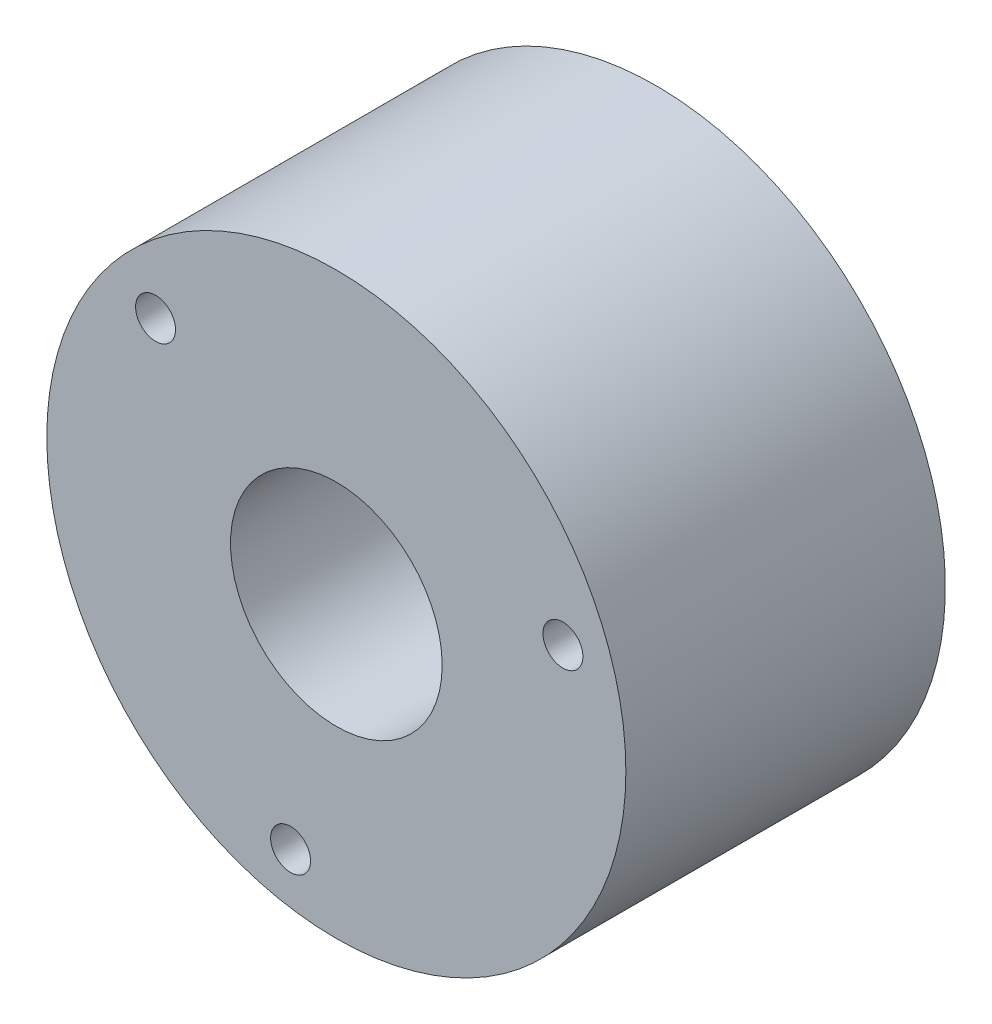
SolidWorks part; units mm, degrees
ref_plane "Ön Düzlem" through (0, 0, 0) normal (0, 0, 1) x (1, 0, 0)
ref_plane "Üst Düzlem" through (0, 0, 0) normal (0, 1, 0) x (1, 0, 0)
ref_plane "Sağ Düzlem" through (0, 0, 0) normal (1, 0, 0) x (0, 0, -1)
sketch "Sketch1" plane through (0, 0, 0) normal (0, 0, 1) x (1, 0, 0)
  circle A0 centre (0, 0) radius 36.25
  circle A1 centre (0, 0) radius 13.25
  dimension "D1" = 72.5
  dimension "D2" = 26.5
extrude "Boss-Extrude1" add sketch "Sketch1" along normal blind 20
sketch "Sketch2" plane through (0, 0, 0) normal (0, 0, -1) x (-1, 0, 0)
  circle A0 centre (0, 0) radius 36.25 construction
  circle A1 centre (0, 0) radius 36.25
  circle A2 centre (0, 0) radius 5.5
  dimension "D1" = 11
extrude "Boss-Extrude3" add sketch "Sketch2" along normal blind 20
sketch "Sketch3" plane through (0, 0, 20) normal (0, 0, 1) x (1, 0, 0)
  circle A0 centre (-5.7315, -29.4474) radius 2.5 construction
  circle A1 centre (-22.6364, 19.6873) radius 2.5 construction
  circle A2 centre (28.368, 9.7601) radius 2.5 construction
  circle A3 centre (-5.7315, -29.4474) radius 2.5
  circle A4 centre (-22.6364, 19.6873) radius 2.5
  circle A5 centre (28.368, 9.7601) radius 2.5
extrude "Cut-Extrude1" cut sketch "Sketch3" against normal through all
